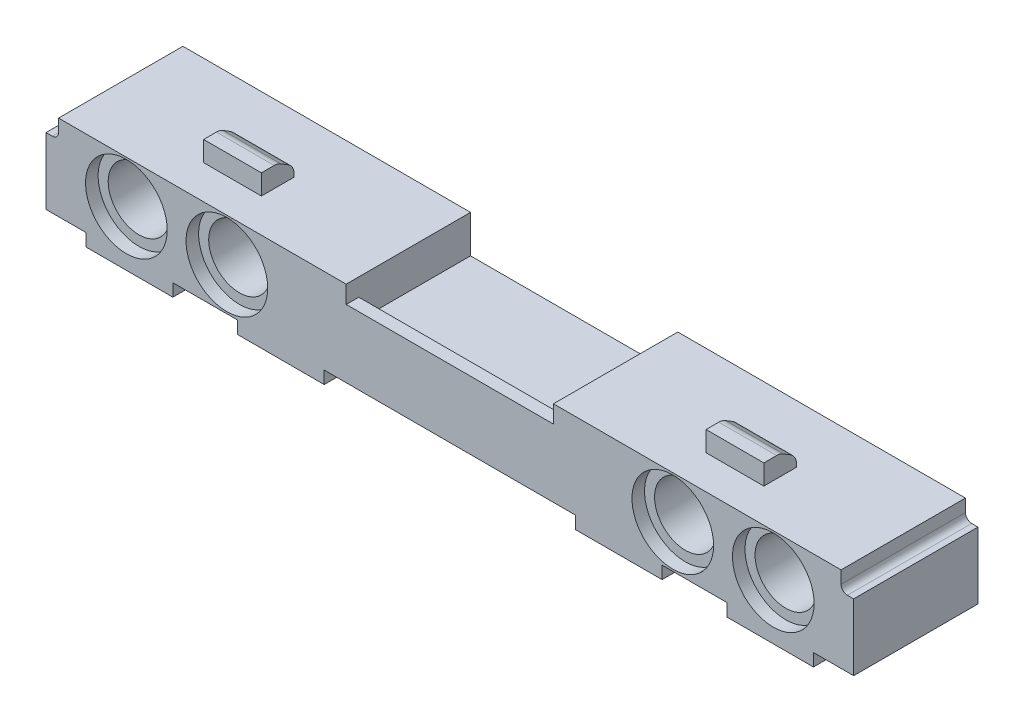
SolidWorks part; units mm, degrees
ref_plane "Front Plane" through (0, 0, 0) normal (0, 0, 1) x (1, 0, 0)
ref_plane "Top Plane" through (0, 0, 0) normal (0, 1, 0) x (1, 0, 0)
ref_plane "Right Plane" through (0, 0, 0) normal (1, 0, 0) x (0, 0, -1)
sketch "Sketch1" plane through (0, 0, 0) normal (0, 0, 1) x (1, 0, 0)
  line L0 (-32.35, -3.6) -> (-32.35, 3.6)
  line L1 (-32.15, -3.4) -> (32.15, -3.4)
  line L2 (-32.15, -3.4) -> (-32.15, 3.4)
  line L3 (-32.15, 3.4) -> (32.15, 3.4)
  line L4 (32.15, -3.4) -> (32.15, 3.4)
  line L5 (-32.15, -3.4) -> (32.15, 3.4) construction
  line L6 (-32.15, 3.4) -> (32.15, -3.4) construction
  line L7 (-32.35, 3.6) -> (32.35, 3.6)
  line L8 (32.35, -3.6) -> (32.35, 3.6)
  line L9 (-32.35, -3.6) -> (32.35, -3.6)
  line L10 (-9.75, 0) -> (9.75, 0)
  line L11 (-9.75, 0) -> (-17.75, 0)
  line L12 (0, 0) -> (0, 2.5241)
  line L13 (-17.75, 0) -> (-25.75, 0)
  line L14 (9.75, 0) -> (17.75, 0)
  line L15 (17.75, 0) -> (25.75, 0)
  circle A1 centre (-17.75, 0) radius 2.45
  circle A2 centre (-25.75, 0) radius 2.45
  circle A4 centre (17.75, 0) radius 2.45
  circle A5 centre (25.75, 0) radius 2.45
  point P0 (0, 0)
  point P13 (0, 0)
  dimension "D7" = 4.9
  dimension "D8" = 4.9
  dimension "D1" = 64.3
  dimension "D2" = 6.8
  dimension "D4" = 19.5
  dimension "D6" = 8
  dimension "D9" = 8
  dimension "D3" = 0.2
extrude "Boss-Extrude2" add sketch "Sketch1" along normal blind 9.9
sketch "Sketch2" plane through (0, 0, 0) normal (0, 0, -1) x (-1, 0, 0)
  line L0 (0, 0) -> (0, -2.1714)
  circle A0 centre (-25.75, 0) radius 3.25
  circle A1 centre (-17.75, 0) radius 3.25
  circle A4 centre (17.75, 0) radius 3.25
  circle A5 centre (25.75, 0) radius 3.25
  dimension "D1" = 6.5
  dimension "D2" = 6.5
extrude "Cut-Extrude1" cut sketch "Sketch2" against normal blind 2.9
sketch "Sketch5" plane through (0, 0, 9.9) normal (0, 0, 1) x (1, 0, 0)
  line L0 (0, 3.4) -> (0, 7.0243)
  line L1 (-32.15, 3.4) -> (-31.15, 3.4)
  line L2 (-32.15, 3.4) -> (-32.15, 1.9)
  line L3 (-32.15, 1.9) -> (-31.65, 1.9)
  line L4 (-31.15, 3.4) -> (-31.15, 2.4)
  line L5 (-32.15, 3.4) -> (32.15, 3.4) construction
  line L6 (31.15, 3.4) -> (31.15, 2.4)
  line L7 (32.15, 1.9) -> (31.65, 1.9)
  line L8 (32.15, 3.4) -> (32.15, 1.9)
  line L9 (32.15, 3.4) -> (31.15, 3.4)
  arc A0 (-31.15, 2.4) -> (-31.65, 1.9) centre (-31.65, 2.4) cw
  arc A1 (31.15, 2.4) -> (31.65, 1.9) centre (31.65, 2.4) ccw
  line M12 (32.15, -3.4) -> (32.15, 3.4)
  line M13 (32.15, 3.4) -> (-32.15, 3.4)
  dimension "D3" = 0.5
  dimension "D1" = 1
  dimension "D2" = 1.5
extrude "Cut-Extrude2" cut sketch "Sketch5" against normal blind 11 contours L6 A1 L7 M12 M13 | L2 L3 A0 L4 L1
sketch "Sketch7" plane through (0, 0, 9.9) normal (0, 0, 1) x (1, 0, 0)
  line L0 (-32.15, -3.4) -> (-28.95, -3.4)
  line L1 (-32.15, -3.4) -> (32.15, -3.4) construction
  line L2 (-22.05, -3.4) -> (-16.9, -3.4)
  line L3 (-28.95, -3.4) -> (-22.05, -3.4)
  line L4 (-28.95, -3.4) -> (-28.95, -4.4)
  line L5 (-28.95, -4.4) -> (-22.05, -4.4)
  line L6 (-22.05, -3.4) -> (-22.05, -4.4)
  line L7 (0, 0) -> (0, 6.5242)
  line L8 (-16.9, -3.4) -> (-10, -3.4)
  line L9 (-16.9, -3.4) -> (-16.9, -4.4)
  line L10 (-16.9, -4.4) -> (-10, -4.4)
  line L11 (-10, -3.4) -> (-10, -4.4)
  line L12 (10, -3.4) -> (10, -4.4)
  line L13 (16.9, -4.4) -> (10, -4.4)
  line L14 (16.9, -3.4) -> (16.9, -4.4)
  line L15 (16.9, -3.4) -> (10, -3.4)
  line L16 (22.05, -3.4) -> (22.05, -4.4)
  line L17 (28.95, -4.4) -> (22.05, -4.4)
  line L18 (28.95, -3.4) -> (28.95, -4.4)
  line L19 (28.95, -3.4) -> (22.05, -3.4)
  line L20 (22.05, -3.4) -> (16.9, -3.4)
  line L21 (32.15, -3.4) -> (28.95, -3.4)
  line M13 (-32.15, -3.4) -> (32.15, -3.4)
  dimension "D1" = 3.2
  dimension "D2" = 6.9
  dimension "D3" = 1
  dimension "D4" = 1
  dimension "D5" = 6.9
  dimension "D6" = 5.15
extrude "Boss-Extrude3" add sketch "Sketch7" against normal up to surface (9.9 mm away) contours L6 L4 L5 M13 | L11 L9 L10 M13 | L14 L12 L13 M13 | L18 L16 L17 M13 up to face at (-22.5, 0, 0)
sketch "Sketch8" plane through (0, 0, 9.9) normal (0, 0, 1) x (1, 0, 0)
  line L0 (-31.15, 3.4) -> (31.15, 3.4) construction
  line L1 (-8.25, 6.4) -> (8.25, 6.4)
  line L2 (-8.25, 6.4) -> (-8.25, 0.4)
  line L3 (-8.25, 0.4) -> (8.25, 0.4)
  line L4 (8.25, 6.4) -> (8.25, 0.4)
  line L5 (-8.25, 6.4) -> (8.25, 0.4) construction
  line L6 (-8.25, 0.4) -> (8.25, 6.4) construction
  point P0 (0, 3.4)
  dimension "D1" = 16.5
  dimension "D2" = 6
extrude "Cut-Extrude3" cut sketch "Sketch8" against normal blind 12
sketch "Sketch9" plane through (0, 0, 9.9) normal (0, 0, 1) x (1, 0, 0)
  line L0 (8.25, 0.4) -> (8.25, 3.4) construction
  line L1 (-8.25, 0.4) -> (8.25, 0.4)
  line L2 (-8.25, 0.4) -> (-8.25, 2)
  line L3 (-8.25, 2) -> (8.25, 2)
  line L4 (8.25, 0.4) -> (8.25, 2)
  dimension "D1" = 1.6
extrude "Boss-Extrude4" add sketch "Sketch9" against normal blind 1 contours L2 L1 L4 L3
sketch "Sketch10" plane through (0, 3.4, 0) normal (0, 1, 0) x (1, 0, 0)
  line L0 (0, -9.9) -> (0, -5.9)
  line L1 (-8.25, -9.9) -> (8.25, -9.9) construction
  line L2 (-20, -5.9) -> (20, -5.9)
  line L4 (-22.3, -7.2) -> (-17.7, -7.2)
  line L5 (-22.3, -7.2) -> (-22.3, -4.6)
  line L6 (-22.3, -4.6) -> (-17.7, -4.6)
  line L7 (-17.7, -7.2) -> (-17.7, -4.6)
  line L8 (-22.3, -7.2) -> (-17.7, -4.6) construction
  line L9 (-22.3, -4.6) -> (-17.7, -7.2) construction
  line L10 (17.7, -7.2) -> (22.3, -7.2)
  line L11 (17.7, -7.2) -> (17.7, -4.6)
  line L12 (17.7, -4.6) -> (22.3, -4.6)
  line L13 (22.3, -7.2) -> (22.3, -4.6)
  line L14 (17.7, -7.2) -> (22.3, -4.6) construction
  line L15 (17.7, -4.6) -> (22.3, -7.2) construction
  point P8 (0, -5.9)
  dimension "D1" = 40
  dimension "D2" = 4.6
  dimension "D3" = 2.6
  dimension "D4" = 4.6
  dimension "D5" = 2.6
  dimension "D6" = 4
extrude "Boss-Extrude5" add sketch "Sketch10" along normal blind 1.6 contours L6 L7 L4 L5 | L12 L13 L10 L11
sketch "Sketch11" plane through (-22.3, 0, 0) normal (-1, 0, 0) x (0, 0, 1)
  line L0 (5.9, 5) -> (4.6, 4.2)
  line L2 (7.2, 5) -> (4.6, 5) construction
  line L4 (4.6, 5) -> (4.6, 3.4) construction
  line L5 (4.6, 4.2) -> (7.2, 4.2)
  line L6 (7.2, 5) -> (7.2, 3.4) construction
  line L7 (7.2, 4.2) -> (7.2, 5)
  line L8 (7.2, 5) -> (5.9, 5)
  line L9 (4.6, 4.2) -> (4.6, 5)
  line L10 (4.6, 5) -> (5.9, 5)
  line M3 (7.2, 5) -> (4.6, 5)
  line M4 (4.6, 5) -> (4.6, 3.4)
extrude "Cut-Extrude4" cut sketch "Sketch11" against normal up to surface (44.6 mm away) contours L0 M3 M4 up to face at (22.3, 4.2, 5.9)
fillet "Fillet1" radius 1 4 edges at (20, 4.2, 4.6) (-20, 4.2, 4.6) (-20, 5, 5.9) (20, 5, 5.9)
sketch "Sketch13" plane through (0, 0, 9.9) normal (0, 0, 1) x (1, 0, 0)
  circle A0 centre (-25.75, 0) radius 3.25
  circle A1 centre (-17.75, 0) radius 3.25
  circle A2 centre (25.75, 0) radius 3.25
  circle A3 centre (17.75, 0) radius 3.25
  dimension "D1" = 6.5
  dimension "D2" = 6.5
  dimension "D3" = 6.5
  dimension "D4" = 6.5
extrude "Cut-Extrude6" cut sketch "Sketch13" against normal blind 1 contours A0 | A1 | A3 | A2
